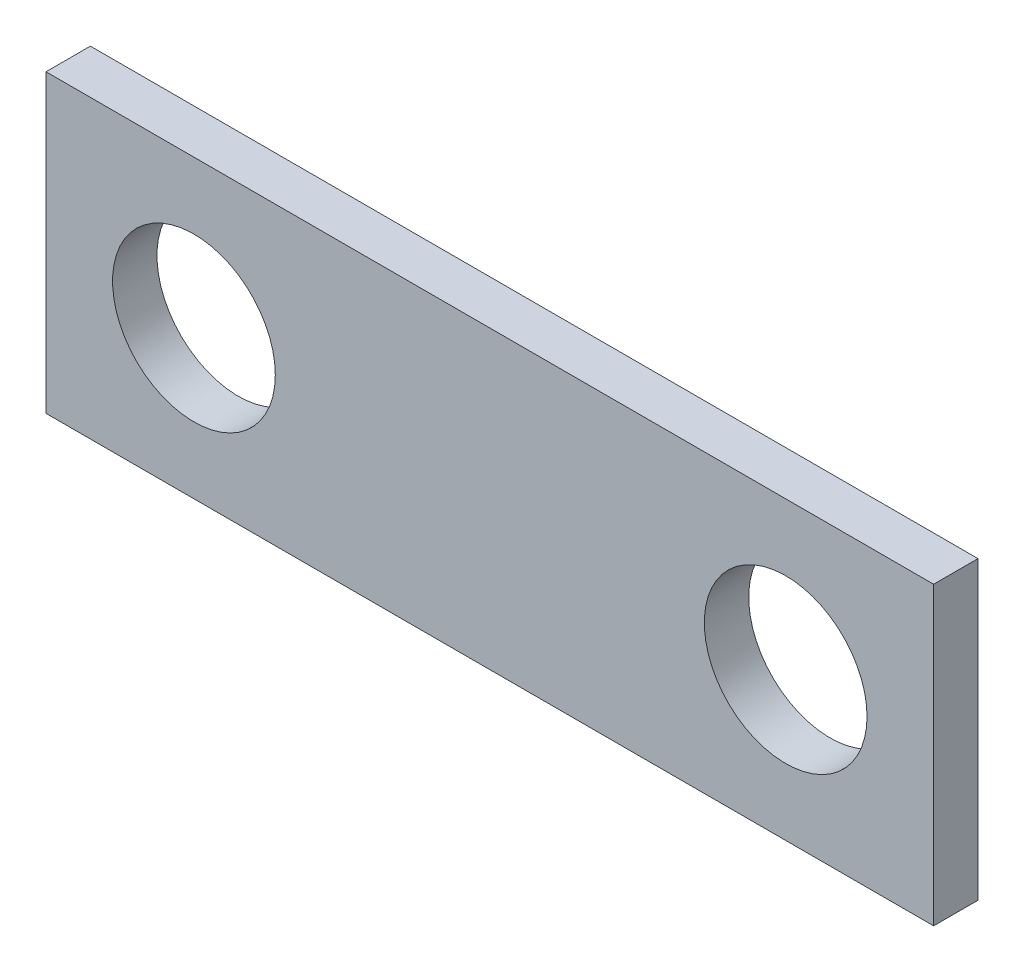
SolidWorks part; units mm, degrees
ref_plane "Alzado" through (0, 0, 0) normal (0, 0, 1) x (1, 0, 0)
ref_plane "Planta" through (0, 0, 0) normal (0, 1, 0) x (1, 0, 0)
ref_plane "Vista lateral" through (0, 0, 0) normal (1, 0, 0) x (0, 0, -1)
sketch "Croquis1" plane through (0, 0, 0) normal (0, 0, 1) x (1, 0, 0)
  line L1 (-30, 10) -> (30, 10)
  line L2 (-30, 10) -> (-30, -10)
  line L3 (-30, -10) -> (30, -10)
  line L4 (30, 10) -> (30, -10)
  line L5 (-30, 10) -> (30, -10) construction
  line L6 (-30, -10) -> (30, 10) construction
  point P0 (0, 0)
  dimension "D1" = 20
  dimension "D2" = 60
extrude "Saliente-Extruir1" add sketch "Croquis1" along normal blind 3
sketch "Croquis2" plane through (0, 0, 3) normal (0, 0, 1) x (1, 0, 0)
  line L0 (30, -10) -> (30, 10) construction
  line L1 (-30, -10) -> (30, -10) construction
  line L2 (-30, 10) -> (-30, -10) construction
  circle A0 centre (-20, 0) radius 5.5
  circle A1 centre (20, 0) radius 5.5
  dimension "D1" = 11
  dimension "D2" = 11
  dimension "D3" = 10
  dimension "D4" = 10
  dimension "D5" = 10
  dimension "D6" = 10
extrude "Cortar-Extruir1" cut sketch "Croquis2" against normal blind 3
